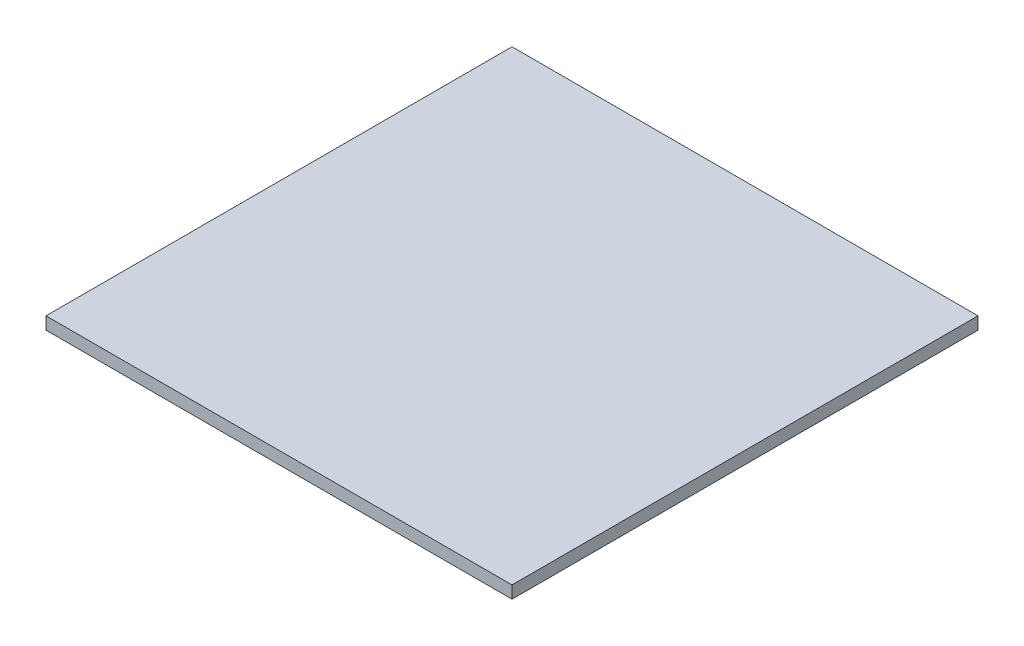
SolidWorks part; units mm, degrees
ref_plane "Front Plane" through (0, 0, 0) normal (0, 0, 1) x (1, 0, 0)
ref_plane "Top Plane" through (0, 0, 0) normal (0, 1, 0) x (1, 0, 0)
ref_plane "Right Plane" through (0, 0, 0) normal (1, 0, 0) x (0, 0, -1)
sketch "Sketch1" plane through (0, 0, 0) normal (0, 1, 0) x (1, 0, 0)
  line L1 (-150, -150) -> (150, -150)
  line L2 (-150, -150) -> (-150, 150)
  line L3 (-150, 150) -> (150, 150)
  line L4 (150, -150) -> (150, 150)
  line L5 (-150, -150) -> (150, 150) construction
  line L6 (-150, 150) -> (150, -150) construction
  point P0 (0, 0)
  dimension "D1" = 300
  dimension "D2" = 300
extrude "Boss-Extrude1" add sketch "Sketch1" along normal blind 8
